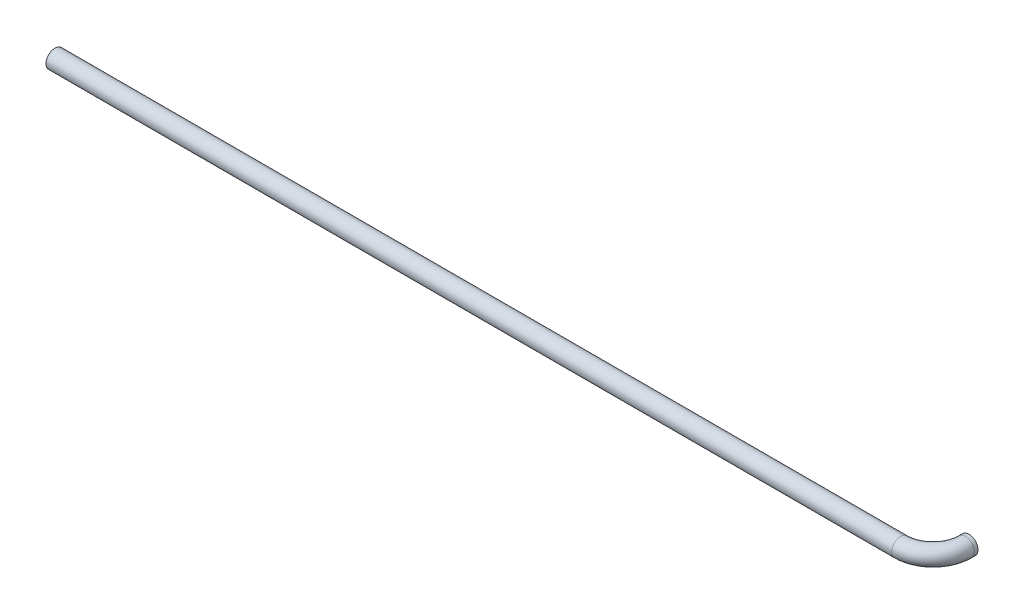
SolidWorks part; units mm, degrees
ref_plane "Front" through (0, 0, 0) normal (0, 0, 1) x (1, 0, 0)
ref_plane "Top" through (0, 0, 0) normal (0, 1, 0) x (1, 0, 0)
ref_plane "Right" through (0, 0, 0) normal (1, 0, 0) x (0, 0, -1)
sketch "Skizze1" plane through (0, 0, 0) normal (1, 0, 0) x (0, 0, -1)
  circle A0 centre (0, 0) radius 1.25
  circle A1 centre (0, 0) radius 1
  dimension "D1" = 2.5
  dimension "D2" = 2
extrude "Aufsatz-Linear austragen1" add sketch "Skizze1" along normal mid plane 117
sketch "Skizze2" plane through (58.5, 0, 0) normal (1, 0, 0) x (0, 0, -1)
  circle A0 centre (0, 0) radius 1 construction
  circle A1 centre (0, 0) radius 1.25
  circle A2 centre (0, 0) radius 1.25
  circle A3 centre (0, 0) radius 1
  dimension "D1" = 0
sketch "Skizze3" plane through (0, 0, 0) normal (0, 1, 0) x (1, 0, 0)
  line L0 (58.5, 0) -> (59, 0)
  line L1 (63.5, 4.5) -> (63.5, 5)
  arc A0 (59, 0) -> (63.5, 4.5) centre (59, 4.5) ccw
  point P7 (63.5, 0)
  dimension "D3" = 4.5
  dimension "D1" = 5
  dimension "D2" = 5
sweep "Austragung1" add profiles "Skizze2" path "Skizze3"
